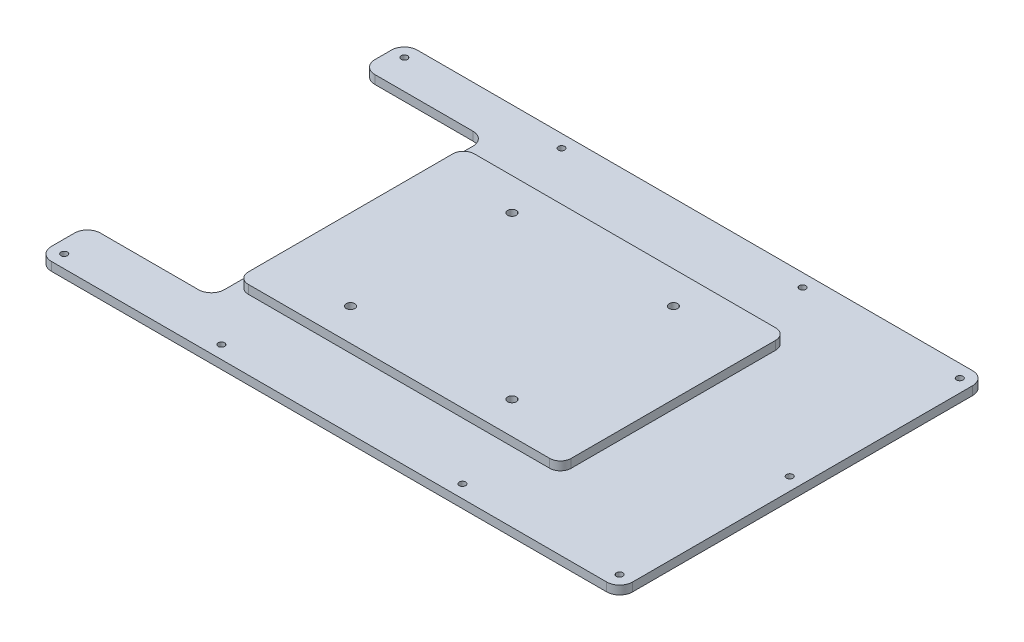
SolidWorks part; units mm, degrees
ref_plane "前视基准面" through (0, 0, 0) normal (0, 0, 1) x (1, 0, 0)
ref_plane "上视基准面" through (0, 0, 0) normal (0, 1, 0) x (1, 0, 0)
ref_plane "右视基准面" through (0, 0, 0) normal (1, 0, 0) x (0, 0, -1)
other "Configuration Table"
sketch "草图1" plane through (0, 0, 0) normal (0, 1, 0) x (1, 0, 0)
  line L0 (-37.5, 90) -> (37.5, 90) construction
  line L1 (-75, 105) -> (75, 105)
  line L2 (-75, 105) -> (-75, 0)
  line L3 (-75, 0) -> (75, 0)
  line L4 (75, 105) -> (75, 0)
  line L5 (37.5, 90) -> (37.5, 15) construction
  line L6 (37.5, 52.5) -> (75, 52.5) construction
  circle A1 centre (-37.5, 90) radius 2
  circle A2 centre (-37.5, 15) radius 2
  circle A3 centre (37.5, 15) radius 2
  circle A4 centre (37.5, 90) radius 2
  point P5 (0, 0)
  point P14 (0, 90)
  dimension "D3" = 75
  dimension "D4" = 4
  dimension "D5" = 75
  dimension "D1" = 150
  dimension "D2" = 105
extrude "凸台-拉伸1" add sketch "草图1" along normal blind 4
sketch "草图2" plane through (0, 0, 0) normal (0, -1, 0) x (1, 0, 0)
  line L0 (75, 0) -> (75, -105) construction
  line L1 (135, -137.5) -> (-135, -137.5)
  line L2 (135, -137.5) -> (135, 32.5)
  line L3 (135, 32.5) -> (-135, 32.5)
  line L4 (-135, -137.5) -> (-135, 32.5)
  point P4 (0, 32.5)
  point P6 (135, -52.5)
  point P9 (75, -52.5)
  dimension "D1" = 170
  dimension "D2" = 270
extrude "凸台-拉伸2" add sketch "草图2" along normal blind 4
sketch "草图3" plane through (0, 4, 0) normal (0, 1, 0) x (1, 0, 0)
  circle A0 centre (-37.5, 90) radius 2
  circle A1 centre (37.5, 90) radius 2
  circle A2 centre (-37.5, 15) radius 2
  circle A3 centre (37.5, 15) radius 2
  point P8 (-37.5, 90)
  point P10 (-37.5, 15)
  point P12 (37.5, 15)
  point P14 (37.5, 90)
  dimension "D1" = 4
extrude "切除-拉伸2" cut sketch "草图3" against normal through all both and the other way through all
fillet "圆角1" radius 6 4 edges at (135, -2, -137.5) (-135, -2, 32.5) (135, -2, 32.5) (-135, -2, -137.5)
sketch "草图4" plane through (0, 0, 0) normal (0, 1, 0) x (1, 0, 0)
  line L0 (-135, 52.5) -> (135, 52.5) construction
  line L1 (-135, -26.5) -> (-135, 131.5) construction
  line L2 (135, 131.5) -> (135, -26.5) construction
  line L3 (0, 137.5) -> (0, 0) construction
  line L4 (-129, 137.5) -> (129, 137.5) construction
  circle A0 centre (-129, 52.5) radius 1.5
  circle A1 centre (-129, 131.5) radius 1.5
  circle A3 centre (-56, 131.5) radius 1.5
  arc A5 (-129, 137.5) -> (-135, 131.5) centre (-129, 131.5) ccw construction
  circle A6 centre (129, 52.5) radius 1.5
  circle A7 centre (129, 52.5) radius 1.5
  circle A8 centre (56, 131.5) radius 1.5
  circle A9 centre (129, 131.5) radius 1.5
  circle A10 centre (129, -26.5) radius 1.5
  circle A11 centre (56, -26.5) radius 1.5
  circle A12 centre (-56, -26.5) radius 1.5
  circle A13 centre (-129, -26.5) radius 1.5
  point P9 (-56.6476, 134.0513)
  point P23 (129, 131.5)
  point P24 (56, 131.5)
  dimension "D2" = 56
  dimension "D3" = 3
  dimension "D1" = 0
extrude "切除-拉伸3" cut sketch "草图4" against normal through all both and the other way through all contours A0 | A13 | A12 | A11 | A10 | A6 | A8 | A9 | A3 | A1
sketch "草图5" plane through (0, 0, 0) normal (0, 1, 0) x (1, 0, 0)
  line L0 (-135, -26.5) -> (-135, 131.5) construction
  line L1 (-135, 117.801) -> (-77.4161, 117.801)
  line L2 (-135, 117.801) -> (-135, -9.7172)
  line L3 (-135, -9.7172) -> (-77.4161, -9.7172)
  line L4 (-77.4161, 117.801) -> (-77.4161, -9.7172)
  point P6 (-86.7705, -11.0636)
  point P7 (-77.4161, -9.7172)
extrude "切除-拉伸4" cut sketch "草图5" against normal through all both and the other way through all
fillet "圆角2" radius 6 4 edges at (-135, -2, -117.801) (-77.4161, -2, -117.801) (-77.4161, -2, 9.7172) (-135, -2, 9.7172)
fillet "圆角3" radius 5 4 edges at (-75, 2, -105) (75, 2, 0) (-75, 2, 0) (75, 2, -105)
sketch "草图6" plane through (0, 0, 0) normal (0, 1, 0) x (1, 0, 0)
  line L1 (-164.2083, 170.3786) -> (171.2923, 170.3786)
  line L2 (-164.2083, 170.3786) -> (-164.2083, -57.1611)
  line L3 (-164.2083, -57.1611) -> (171.2923, -57.1611)
  line L4 (171.2923, 170.3786) -> (171.2923, -57.1611)
extrude "切除-拉伸5" [suppressed] cut sketch "草图6" against normal through all
